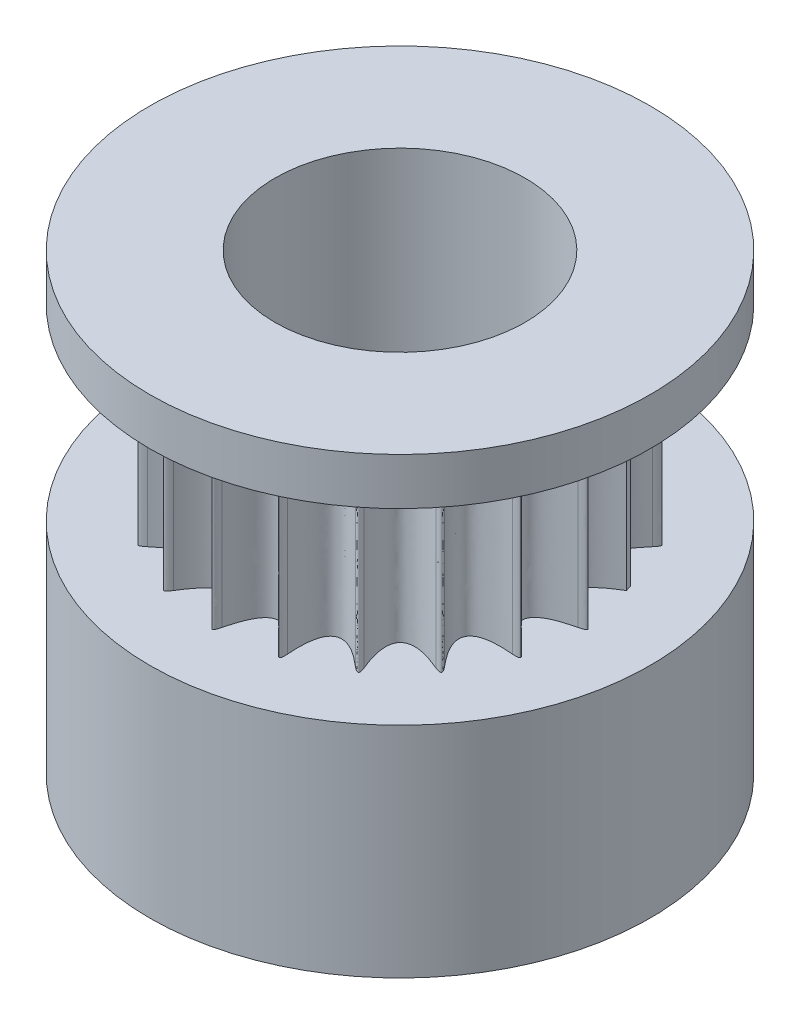
SolidWorks part; units mm, degrees
material "1060 Alloy"
ref_plane "Front Plane" through (0, 0, 0) normal (0, 0, 1) x (1, 0, 0)
ref_plane "Top Plane" through (0, 0, 0) normal (0, 1, 0) x (1, 0, 0)
ref_plane "Right Plane" through (0, 0, 0) normal (1, 0, 0) x (0, 0, -1)
sketch "Sketch1" plane through (0, 0, 0) normal (0, 1, 0) x (1, 0, 0)
  circle A0 centre (0, 0) radius 8
  dimension "D1" = 16
extrude "Boss-Extrude1" add sketch "Sketch1" along normal blind 7
sketch "Sketch2" plane through (0, 7, 0) normal (0, 1, 0) x (1, 0, 0)
  line L0 (0, 8) -> (0, 6) construction
  line L1 (8, 0) -> (6, 0) construction
  line L21 (5.5161, 1.7923) -> (5.7063, 1.8541)
  line L22 (5.7063, 1.8541) -> (5.5161, 1.7923)
  line L23 (5.5161, 1.7923) -> (5.547, 1.6972)
  line L24 (5.5161, 1.7923) -> (5.4852, 1.8874)
  line L25 (-6, 0) -> (-8, 0) construction
  line L31 (0, -6) -> (0, -8) construction
  circle A0 centre (0, 0) radius 8 construction
  circle A1 centre (0, 0) radius 6
  spline S0 degree 2 poles (5.4852, 1.8874) (5.8966, 1.9159) (5.547, 1.6972) knots 0 0 0 1 1 1
  spline S1 degree 2 poles (5.8, 0.1) (6.2, 0) (5.8, -0.1) knots 0 0 0 1 1 1
  spline S2 degree 2 poles (5.547, -1.6972) (5.8966, -1.9159) (5.4852, -1.8874) knots 0 0 0 1 1 1
  spline S3 degree 2 poles (4.7511, -3.3283) (5.0159, -3.6443) (4.6335, -3.4901) knots 0 0 0 1 1 1
  spline S4 degree 2 poles (3.4901, -4.6335) (3.6443, -5.0159) (3.3283, -4.7511) knots 0 0 0 1 1 1
  spline S5 degree 2 poles (1.8874, -5.4852) (1.9159, -5.8966) (1.6972, -5.547) knots 0 0 0 1 1 1
  spline S6 degree 2 poles (0.1, -5.8) (0, -6.2) (-0.1, -5.8) knots 0 0 0 1 1 1
  spline S7 degree 2 poles (-1.6972, -5.547) (-1.9159, -5.8966) (-1.8874, -5.4852) knots 0 0 0 1 1 1
  spline S8 degree 2 poles (-3.3283, -4.7511) (-3.6443, -5.0159) (-3.4901, -4.6335) knots 0 0 0 1 1 1
  spline S9 degree 2 poles (-4.6335, -3.4901) (-5.0159, -3.6443) (-4.7511, -3.3283) knots 0 0 0 1 1 1
  spline S10 degree 2 poles (-5.4852, -1.8874) (-5.8966, -1.9159) (-5.547, -1.6972) knots 0 0 0 1 1 1
  spline S11 degree 2 poles (-5.8, -0.1) (-6.2, 0) (-5.8, 0.1) knots 0 0 0 1 1 1
  spline S12 degree 2 poles (-5.547, 1.6972) (-5.8966, 1.9159) (-5.4852, 1.8874) knots 0 0 0 1 1 1
  spline S13 degree 2 poles (-4.7511, 3.3283) (-5.0159, 3.6443) (-4.6335, 3.4901) knots 0 0 0 1 1 1
  spline S14 degree 2 poles (-3.4901, 4.6335) (-3.6443, 5.0159) (-3.3283, 4.7511) knots 0 0 0 1 1 1
  spline S15 degree 2 poles (-1.8874, 5.4852) (-1.9159, 5.8966) (-1.6972, 5.547) knots 0 0 0 1 1 1
  spline S16 degree 2 poles (-0.1, 5.8) (0, 6.2) (0.1, 5.8) knots 0 0 0 1 1 1
  spline S17 degree 2 poles (1.6972, 5.547) (1.9159, 5.8966) (1.8874, 5.4852) knots 0 0 0 1 1 1
  spline S18 degree 2 poles (3.3283, 4.7511) (3.6443, 5.0159) (3.4901, 4.6335) knots 0 0 0 1 1 1
  spline S19 degree 2 poles (4.6335, 3.4901) (5.0159, 3.6443) (4.7511, 3.3283) knots 0 0 0 1 1 1
  spline S20 degree 2 poles (5.547, 1.6972) (3.7236, 0.6081) (5.8, 0.1) knots 0 0 0 1 1 1
  spline S21 degree 2 poles (5.8, -0.1) (3.7292, -0.5723) (5.547, -1.6972) knots 0 0 0 1 1 1
  spline S22 degree 2 poles (5.4852, -1.8874) (3.3699, -1.6967) (4.7511, -3.3283) knots 0 0 0 1 1 1
  spline S23 degree 2 poles (4.6335, -3.4901) (2.6807, -2.655) (3.4901, -4.6335) knots 0 0 0 1 1 1
  spline S24 degree 2 poles (3.3283, -4.7511) (1.729, -3.3534) (1.8874, -5.4852) knots 0 0 0 1 1 1
  spline S25 degree 2 poles (1.6972, -5.547) (0.6081, -3.7236) (0.1, -5.8) knots 0 0 0 1 1 1
  spline S26 degree 2 poles (-0.1, -5.8) (-0.5723, -3.7292) (-1.6972, -5.547) knots 0 0 0 1 1 1
  spline S27 degree 2 poles (-1.8874, -5.4852) (-1.6967, -3.3699) (-3.3283, -4.7511) knots 0 0 0 1 1 1
  spline S28 degree 2 poles (-3.4901, -4.6335) (-2.655, -2.6807) (-4.6335, -3.4901) knots 0 0 0 1 1 1
  spline S29 degree 2 poles (-4.7511, -3.3283) (-3.3534, -1.729) (-5.4852, -1.8874) knots 0 0 0 1 1 1
  spline S30 degree 2 poles (-5.547, -1.6972) (-3.7236, -0.6081) (-5.8, -0.1) knots 0 0 0 1 1 1
  spline S31 degree 2 poles (-5.8, 0.1) (-3.7292, 0.5723) (-5.547, 1.6972) knots 0 0 0 1 1 1
  spline S32 degree 2 poles (-5.4852, 1.8874) (-3.3699, 1.6967) (-4.7511, 3.3283) knots 0 0 0 1 1 1
  spline S33 degree 2 poles (-4.6335, 3.4901) (-2.6807, 2.655) (-3.4901, 4.6335) knots 0 0 0 1 1 1
  spline S34 degree 2 poles (-3.3283, 4.7511) (-1.729, 3.3534) (-1.8874, 5.4852) knots 0 0 0 1 1 1
  spline S35 degree 2 poles (-1.6972, 5.547) (-0.6081, 3.7236) (-0.1, 5.8) knots 0 0 0 1 1 1
  spline S36 degree 2 poles (0.1, 5.8) (0.5723, 3.7292) (1.6972, 5.547) knots 0 0 0 1 1 1
  spline S37 degree 2 poles (1.8874, 5.4852) (1.6967, 3.3699) (3.3283, 4.7511) knots 0 0 0 1 1 1
  spline S38 degree 2 poles (3.4901, 4.6335) (2.655, 2.6807) (4.6335, 3.4901) knots 0 0 0 1 1 1
  spline S39 degree 2 poles (4.7511, 3.3283) (3.3534, 1.729) (5.4852, 1.8874) knots 0 0 0 1 1 1
  point P32 (0, 0)
  point P94 (0, 0)
  point P153 (0, 0)
  dimension "D1" = 12
  dimension "D3" = 0.1
  dimension "D4" = 0.1
  dimension "D5" = 0.2
extrude "Boss-Extrude2" add sketch "Sketch2" along normal blind 6 contours S39 S19 S38 S18 S37 S17 S36 S16 S35 S15 S34 S14 S33 S13 S32 S12 S31 S11 S30 S10 S29 S9 S28 S8 S27 S7 S26 S6 S25 S5 S24 S4 S23 S3
sketch "Sketch3" plane through (0, 13, 0) normal (0, 1, 0) x (1, 0, 0)
  circle A0 centre (0, 0) radius 8 construction
  circle A1 centre (0, 0) radius 8
extrude "Boss-Extrude3" add sketch "Sketch3" along normal blind 1.5
sketch "Sketch4" plane through (0, 14.5, 0) normal (0, 1, 0) x (1, 0, 0)
  circle A0 centre (0, 0) radius 4
  dimension "D1" = 8
extrude "Cut-Extrude1" cut sketch "Sketch4" against normal through all
